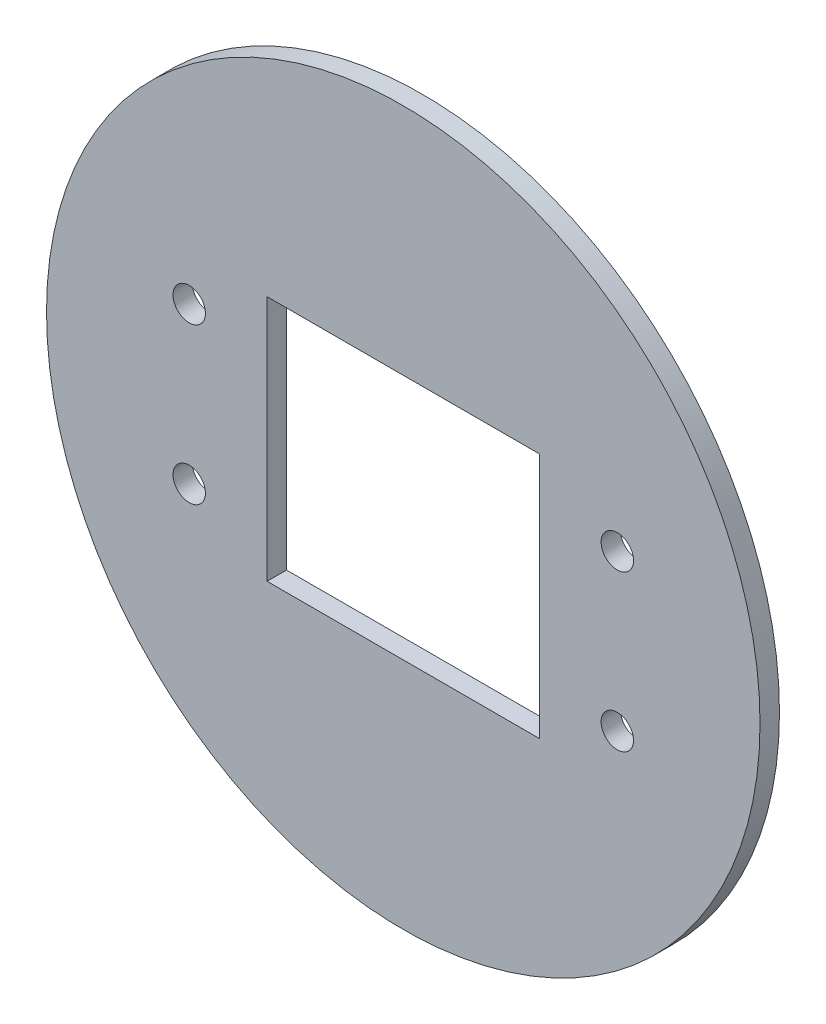
SolidWorks part; units mm, degrees
ref_plane "前视基准面" through (0, 0, 0) normal (0, 0, 1) x (1, 0, 0)
ref_plane "上视基准面" through (0, 0, 0) normal (0, 1, 0) x (1, 0, 0)
ref_plane "右视基准面" through (0, 0, 0) normal (1, 0, 0) x (0, 0, -1)
sketch "草图2" plane through (0, 0, 0) normal (0, 0, 1) x (1, 0, 0)
  line L1 (-10.5, 9.5) -> (10.5, 9.5)
  line L2 (-10.5, 9.5) -> (-10.5, -9.5)
  line L3 (-10.5, -9.5) -> (10.5, -9.5)
  line L4 (10.5, 9.5) -> (10.5, -9.5)
  line L5 (-10.5, 9.5) -> (10.5, -9.5) construction
  line L6 (-10.5, -9.5) -> (10.5, 9.5) construction
  circle A0 centre (0, 0) radius 27.5
  dimension "D1" = 55
  dimension "D2" = 19
  dimension "D3" = 21
extrude "凸台-拉伸2" add sketch "草图2" along normal blind 1.5 contours L2 L3 L4 L1 | A0
sketch "草图3" plane through (0, 0, 1.5) normal (0, 0, 1) x (1, 0, 0)
  line L0 (10.5, 9.5) -> (10.5, -9.5) construction
  line L2 (0.825, 0) -> (-0.825, 0) construction
  line L3 (0, -0.825) -> (0, 0.825) construction
  circle A0 centre (16.5, 6) radius 1.25
  circle A1 centre (-16.5, 6) radius 1.25
  circle A2 centre (16.5, -6) radius 1.25
  circle A3 centre (-16.5, -6) radius 1.25
  point P6 (29.2262, 17.2667)
  dimension "D1" = 6
  dimension "D2" = 6
extrude "切除-拉伸1" cut sketch "草图3" against normal blind 10
